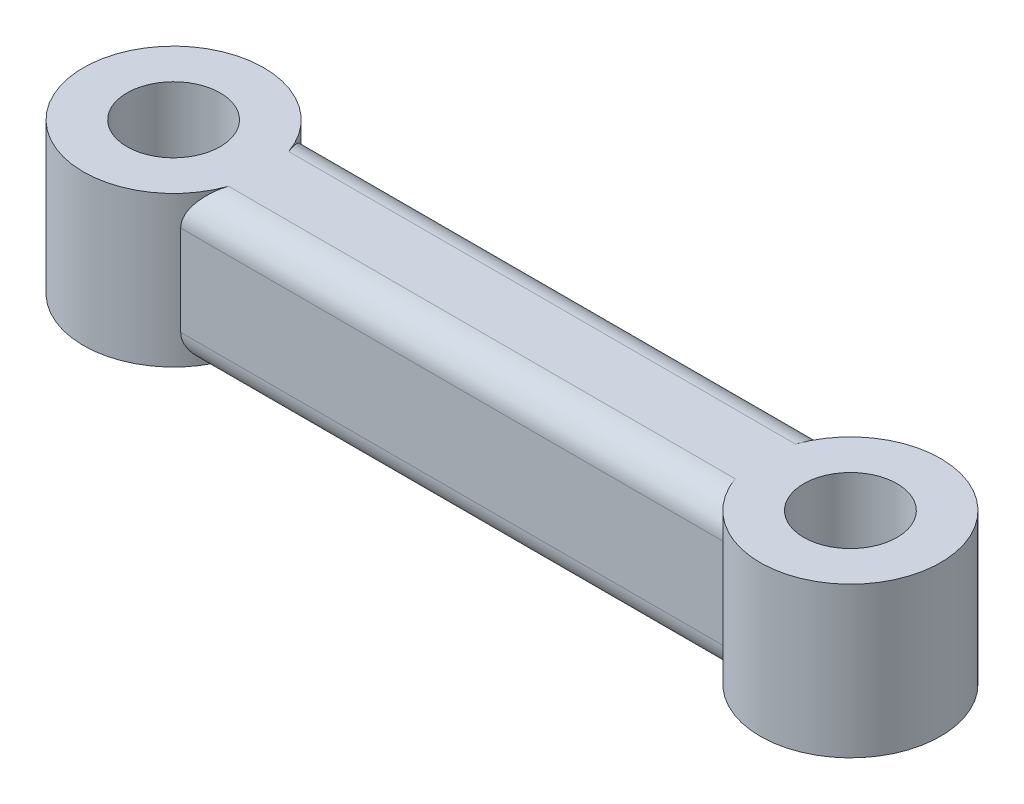
SolidWorks part; units mm, degrees
ref_plane "Спереди" through (0, 0, 0) normal (0, 0, 1) x (1, 0, 0)
ref_plane "Сверху" through (0, 0, 0) normal (0, 1, 0) x (1, 0, 0)
ref_plane "Справа" through (0, 0, 0) normal (1, 0, 0) x (0, 0, -1)
sketch "Эскиз1" plane through (0, 0, 0) normal (0, 1, 0) x (1, 0, 0)
  line L0 (-227.0445, 0) -> (11125.1801, 0) construction
  line L2 (-9.0139, 2) -> (9.0139, 2)
  line L4 (-9.0139, -2) -> (9.0139, -2)
  arc A0 (-9.0139, 2) -> (-9.0139, -2) centre (-11.25, 0) ccw
  arc A1 (9.0139, -2) -> (9.0139, 2) centre (11.25, 0) ccw
  circle A2 centre (-11.25, 0) radius 1.55
  circle A3 centre (11.25, 0) radius 1.55
  point P4 (0, 2)
  dimension "D1" = 22.5
  dimension "D2" = 3.1
  dimension "D3" = 6
  dimension "D4" = 4
extrude "Бобышка-Вытянуть1" add sketch "Эскиз1" along normal blind 5
fillet "Скругление1" radius 1 4 edges at (0, 0, -2) (0, 0, 2) (0, 5, -2) (0, 5, 2)
